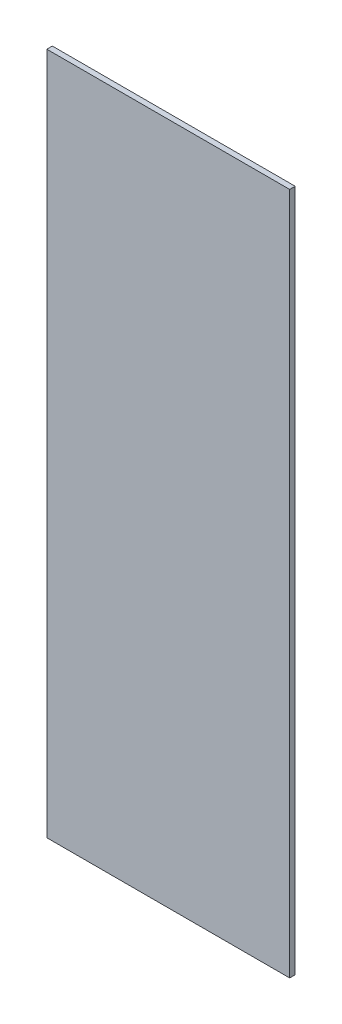
SolidWorks part; units mm, degrees
material "Acrylic (Medium-high impact)"
ref_plane "Front Plane" through (0, 0, 0) normal (0, 0, 1) x (1, 0, 0)
ref_plane "Top Plane" through (0, 0, 0) normal (0, 1, 0) x (1, 0, 0)
ref_plane "Right Plane" through (0, 0, 0) normal (1, 0, 0) x (0, 0, -1)
sketch "Sketch1" plane through (0, 0, 0) normal (0, 0, 1) x (1, 0, 0)
  line L1 (132.5, -372.5) -> (-132.5, -372.5)
  line L2 (132.5, -372.5) -> (132.5, 372.5)
  line L3 (132.5, 372.5) -> (-132.5, 372.5)
  line L4 (-132.5, -372.5) -> (-132.5, 372.5)
  line L5 (132.5, -372.5) -> (-132.5, 372.5) construction
  line L6 (132.5, 372.5) -> (-132.5, -372.5) construction
  point P0 (0, 0)
  dimension "D1" = 745
  dimension "D2" = 265
extrude "Boss-Extrude1" add sketch "Sketch1" along normal blind 6
